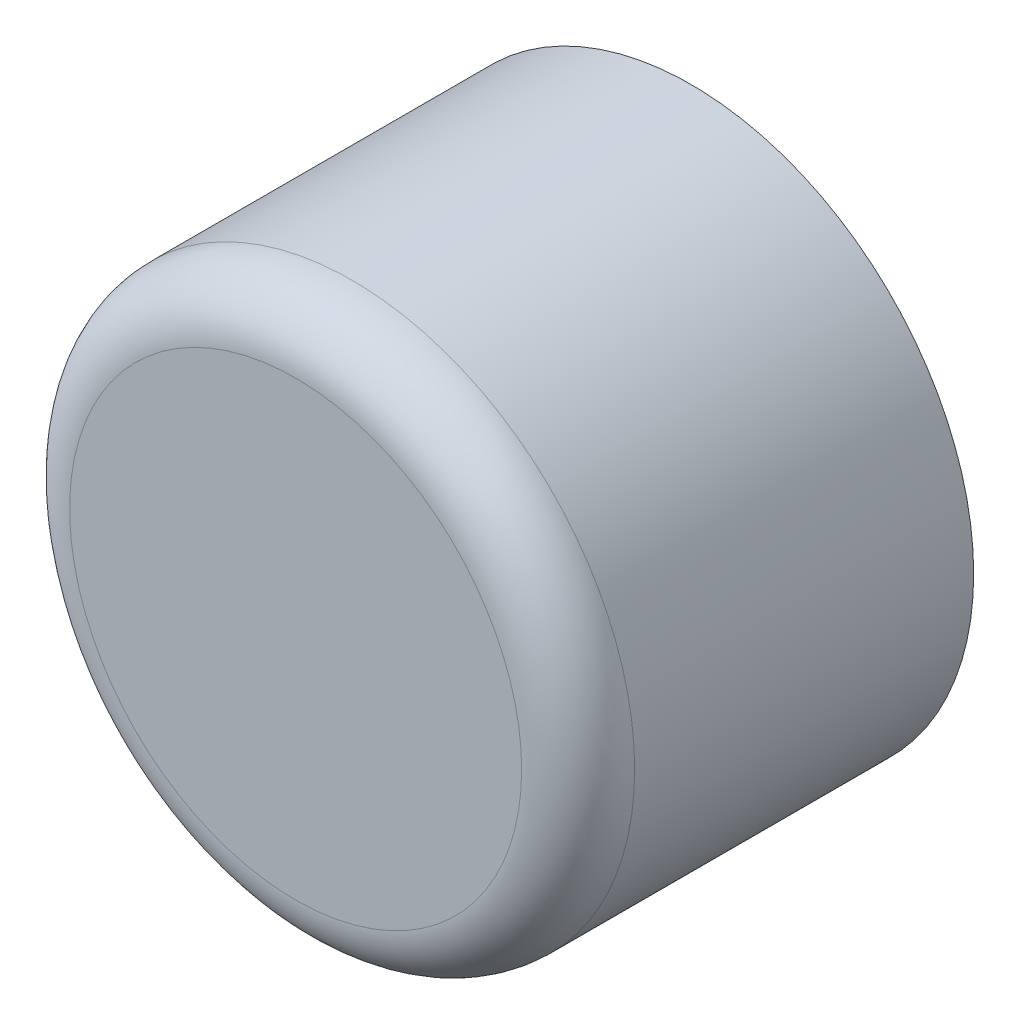
SolidWorks part; units mm, degrees
ref_plane "Front Plane" through (0, 0, 0) normal (0, 0, 1) x (1, 0, 0)
ref_plane "Top Plane" through (0, 0, 0) normal (0, 1, 0) x (1, 0, 0)
ref_plane "Right Plane" through (0, 0, 0) normal (1, 0, 0) x (0, 0, -1)
sketch "Sketch3" plane through (0, 0, 2.9718) normal (0, 0, 1) x (1, 0, 0)
  circle A0 centre (30.4184, -58.0984) radius 5
extrude "Boss-Extrude2" add sketch "Sketch3" along normal blind 5
sketch "Sketch4" plane through (0, 0, 2.9718) normal (0, 0, -1) x (-1, 0, 0)
  line L0 (-30.5053, -60.7551) -> (-33.0751, -58.0114)
  line L1 (-33.0751, -58.0114) -> (-30.3314, -55.4416)
  line L2 (-30.3314, -55.4416) -> (-27.7617, -58.1853)
  line L3 (-27.7617, -58.1853) -> (-30.5053, -60.7551)
  circle A0 centre (-30.4184, -58.0984) radius 5 construction
  circle A1 centre (-30.4184, -58.0984) radius 5
extrude "Boss-Extrude3" add sketch "Sketch4" along normal blind 2
sketch "Sketch5" plane through (-13.4875, -14.4003, 0) normal (-0.6836, -0.7299, 0) x (0.7299, -0.6836, 0)
  line L4 (63.7966, 2.9718) -> (60.0374, 2.9718)
  line L5 (60.0374, 2.9718) -> (60.0374, 0.9718)
  line L6 (60.0374, 0.9718) -> (63.7966, 0.9718)
  line L7 (63.7966, 0.9718) -> (63.7966, 2.9718)
  line L8 (63.7966, 2.9718) -> (60.0374, 2.9718)
  line L9 (60.0374, 2.9718) -> (60.0374, 0.9718)
  line L10 (60.0374, 0.9718) -> (63.7966, 0.9718)
  line L11 (63.7966, 0.9718) -> (63.7966, 2.9718)
  dimension "D1" = 0
extrude "Cut-Extrude2" cut sketch "Sketch5" against normal blind 0.5
sketch "Sketch6" plane through (-16.0573, -17.144, 0) normal (0.6836, 0.7299, 0) x (0.7299, -0.6836, 0)
  line L4 (60.0374, -2.9718) -> (63.7966, -2.9718)
  line L5 (63.7966, -2.9718) -> (63.7966, -0.9718)
  line L6 (63.7966, -0.9718) -> (60.0374, -0.9718)
  line L7 (60.0374, -0.9718) -> (60.0374, -2.9718)
  line L8 (60.0374, -2.9718) -> (63.7966, -2.9718)
  line L9 (63.7966, -2.9718) -> (63.7966, -0.9718)
  line L10 (63.7966, -0.9718) -> (60.0374, -0.9718)
  line L11 (60.0374, -0.9718) -> (60.0374, -2.9718)
  dimension "D1" = 0
extrude "Cut-Extrude3" cut sketch "Sketch6" against normal blind 0.5
sketch "Sketch7" plane through (43.8189, -41.0413, 0) normal (0.7299, -0.6836, 0) x (0, 0, -1)
  line L4 (-2.9718, -19.2302) -> (-2.9718, -23.9894)
  line L5 (-2.9718, -23.9894) -> (-0.9718, -23.9894)
  line L6 (-0.9718, -23.9894) -> (-0.9718, -19.2302)
  line L7 (-0.9718, -19.2302) -> (-2.9718, -19.2302)
  line L8 (-2.9718, -19.2302) -> (-2.9718, -23.9894)
  line L9 (-2.9718, -23.9894) -> (-0.9718, -23.9894)
  line L10 (-0.9718, -23.9894) -> (-0.9718, -19.2302)
  line L11 (-0.9718, -19.2302) -> (-2.9718, -19.2302)
  dimension "D1" = 0
extrude "Cut-Extrude4" cut sketch "Sketch7" against normal blind 0.5
sketch "Sketch8" plane through (46.5626, -43.6111, 0) normal (-0.7299, 0.6836, 0) x (0, 0, 1)
  line L4 (2.9718, -23.9894) -> (2.9718, -19.2302)
  line L5 (2.9718, -19.2302) -> (0.9718, -19.2302)
  line L6 (0.9718, -19.2302) -> (0.9718, -23.9894)
  line L7 (0.9718, -23.9894) -> (2.9718, -23.9894)
  line L8 (2.9718, -23.9894) -> (2.9718, -19.2302)
  line L9 (2.9718, -19.2302) -> (0.9718, -19.2302)
  line L10 (0.9718, -19.2302) -> (0.9718, -23.9894)
  line L11 (0.9718, -23.9894) -> (2.9718, -23.9894)
  dimension "D1" = 0
extrude "Cut-Extrude5" cut sketch "Sketch8" against normal blind 0.5
fillet "Fillet1" radius 1 1 edges at (35.4184, -58.0984, 7.9718)
